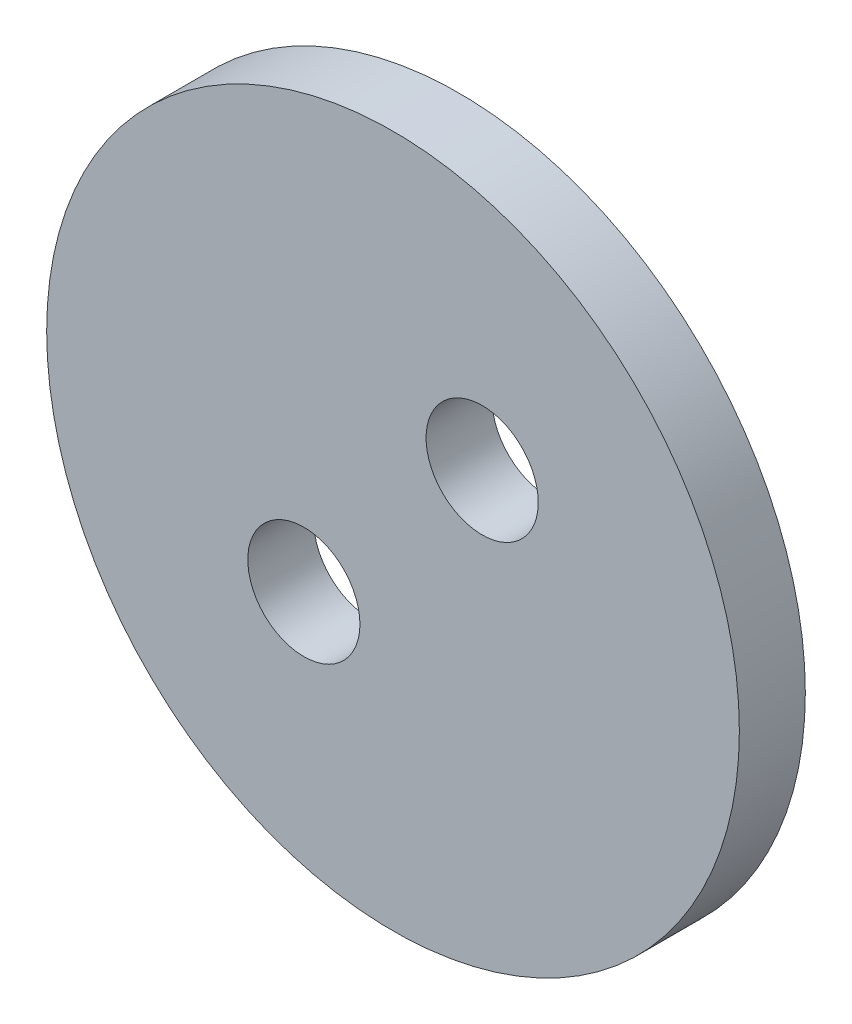
SolidWorks part; units mm, degrees
material "Сплав 2024"
ref_plane "Спереди" through (0, 0, 0) normal (0, 0, 1) x (1, 0, 0)
ref_plane "Сверху" through (0, 0, 0) normal (0, 1, 0) x (1, 0, 0)
ref_plane "Справа" through (0, 0, 0) normal (1, 0, 0) x (0, 0, -1)
sketch "Эскиз1" plane through (0, 0, 0) normal (0, 0, 1) x (1, 0, 0)
  circle A0 centre (0, 0) radius 10.5
  dimension "D1" = 21
extrude "Бобышка-Вытянуть1" add sketch "Эскиз1" along normal blind 2
sketch "Эскиз2" plane through (0, 0, 2) normal (0, 0, 1) x (1, 0, 0)
  line L0 (-2.9491, 2.7024) -> (2.9491, -2.7024) construction
  line L1 (2.7024, 2.9491) -> (-2.7024, -2.9491) construction
  circle A0 centre (0, 0) radius 4 construction
  dimension "D1" = 8
hole_wizard "Отверстие с зазором M31" positions "Эскиз4" profile "Эскиз3" hole size "M3" standard "Ansi Metric" end condition through all
sketch "Эскиз4" plane through (0, 0, 2) normal (0, 0, 1) x (1, 0, 0)
  point P0 (2.7024, 2.9491)
  point P3 (-2.7024, -2.9491)
sketch "Эскиз3" plane through (2.7024, 2.9491, 2) normal (1, 0, 0) x (0, -1, 0)
  line L0 (0, 0) -> (0, 2)
  line L1 (0, 2) -> (1.7, 2)
  line L2 (1.7, 2) -> (1.7, 0)
  line L5 (1.7, 0) -> (0, 0)
  line L11 (0, -6.35) -> (0, 107.95) construction
  dimension "Диаметр сквозного отверстия" = 3.4
  dimension "Глубина сквозного отверстия" = 2
